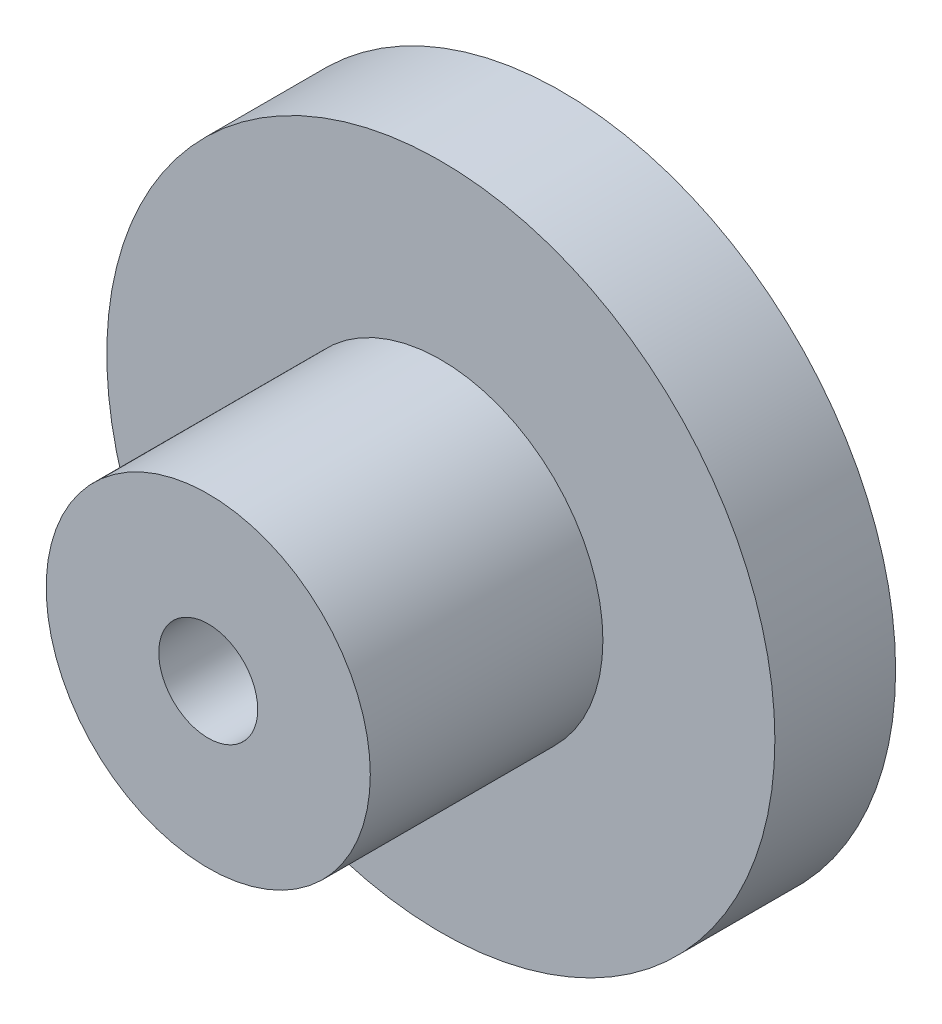
SolidWorks part; units mm, degrees
ref_plane "前视基准面" through (0, 0, 0) normal (0, 0, 1) x (1, 0, 0)
ref_plane "上视基准面" through (0, 0, 0) normal (0, 1, 0) x (1, 0, 0)
ref_plane "右视基准面" through (0, 0, 0) normal (1, 0, 0) x (0, 0, -1)
sketch "草图1" plane through (0, 0, 0) normal (0, 0, 1) x (1, 0, 0)
  circle A0 centre (0, 0) radius 6.75
  dimension "D1" = 13.5
extrude "T32-0.4" add sketch "草图1" along normal blind 2.44
sketch "草图2" plane through (0, 0, 2.44) normal (0, 0, 1) x (1, 0, 0)
  circle A0 centre (0, 0) radius 3.275
  dimension "D1" = 6.55
extrude "T14-0.4" add sketch "草图2" along normal blind 4.7
sketch "草图3" plane through (0, 0, 7.14) normal (0, 0, 1) x (1, 0, 0)
  circle A0 centre (0, 0) radius 1
  dimension "D1" = 2
extrude "切除-拉伸1" cut sketch "草图3" against normal through all
